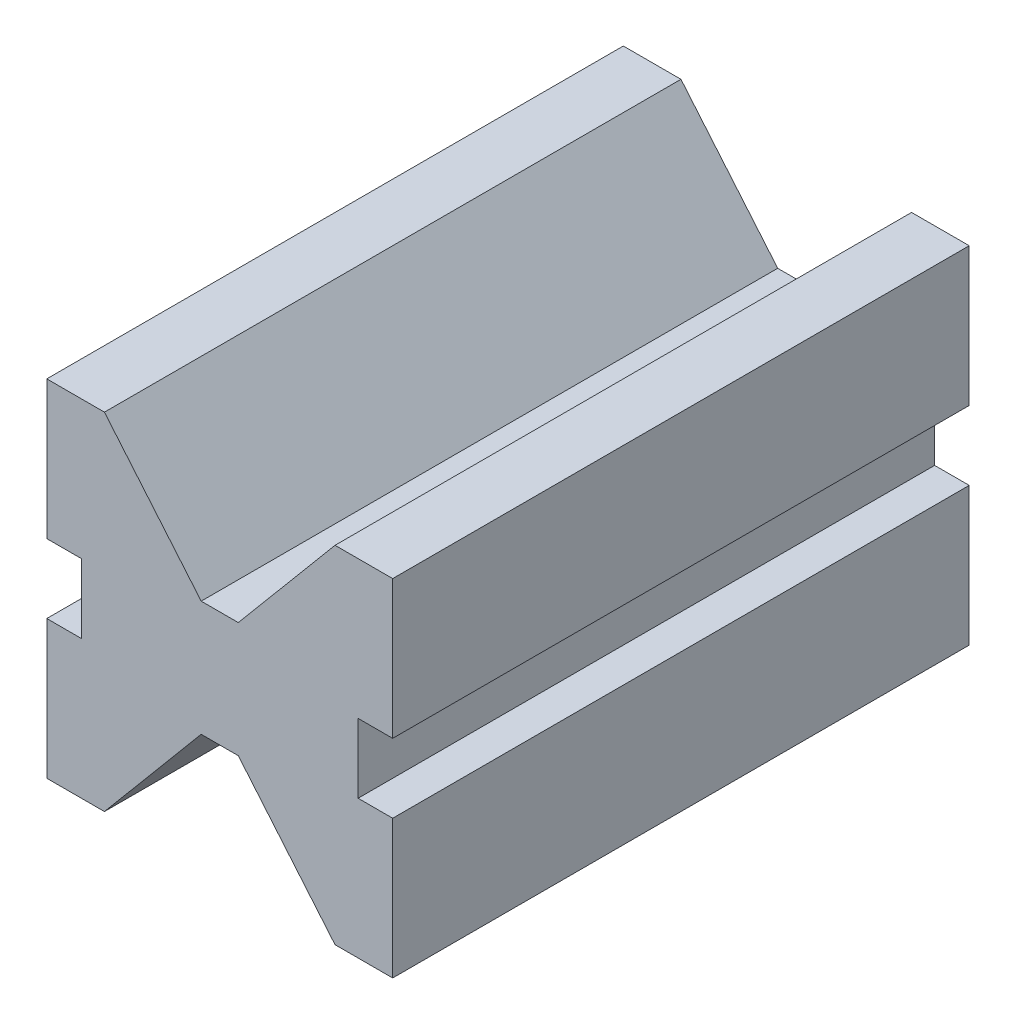
SolidWorks part; units mm, degrees
material "Polietereterketon (PEEK)"
ref_plane "Ön Düzlem" through (0, 0, 0) normal (0, 0, 1) x (1, 0, 0)
ref_plane "Üst Düzlem" through (0, 0, 0) normal (0, 1, 0) x (1, 0, 0)
ref_plane "Sağ Düzlem" through (0, 0, 0) normal (1, 0, 0) x (0, 0, -1)
sketch "Çizim2" plane through (0, 0, 0) normal (0, 0, 1) x (1, 0, 0)
  line L0 (0, 30) -> (0, 0) construction
  line L1 (-30, 30) -> (-20, 30)
  line L2 (-30, 30) -> (-30, 6)
  line L3 (-30, -30) -> (-20, -30)
  line L4 (30, 30) -> (30, 6)
  line L5 (-30, 30) -> (30, -30) construction
  line L6 (-30, -30) -> (30, 30) construction
  line L7 (0, 0) -> (-30, 0) construction
  line L8 (-20, 30) -> (-3.218, 10)
  line L9 (-3.218, 10) -> (3.218, 10)
  line L10 (3.218, 10) -> (20, 30)
  line L11 (-20, -30) -> (-3.218, -10)
  line L12 (-3.218, -10) -> (3.218, -10)
  line L13 (3.218, -10) -> (20, -30)
  line L14 (-30, 6) -> (-24, 6)
  line L15 (-24, 6) -> (-24, -6)
  line L16 (-24, -6) -> (-30, -6)
  line L17 (24, -6) -> (30, -6)
  line L18 (24, 6) -> (24, -6)
  line L19 (30, 6) -> (24, 6)
  line L20 (-30, -6) -> (-30, -30)
  line L21 (30, -6) -> (30, -30)
  line L22 (20, 30) -> (30, 30)
  line L23 (20, -30) -> (30, -30)
  point P0 (0, 0)
  dimension "D1" = 20
  dimension "D2" = 60
  dimension "D3" = 40
  dimension "D4" = 50
  dimension "D5" = 12
  dimension "D6" = 6
extrude "Yükseklik-Ekstrüzyon1" add sketch "Çizim2" along normal blind 100
